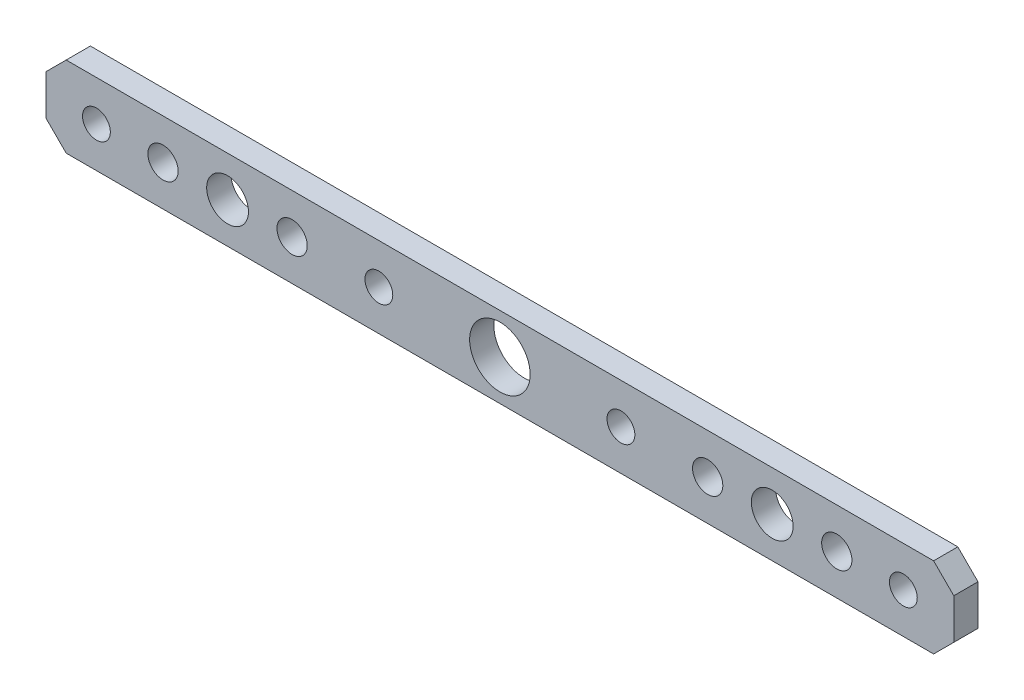
SolidWorks part; units mm, degrees
ref_plane "Front Plane" through (0, 0, 0) normal (0, 0, 1) x (1, 0, 0)
ref_plane "Top Plane" through (0, 0, 0) normal (0, 1, 0) x (1, 0, 0)
ref_plane "Right Plane" through (0, 0, 0) normal (1, 0, 0) x (0, 0, -1)
sketch "Sketch1" plane through (0, 0, 0) normal (0, 0, 1) x (1, 0, 0)
  line L0 (-111.9828, -29.6121) -> (113.0172, -29.6121)
  line L1 (113.0172, -29.6121) -> (113.0172, -9.6121)
  line L3 (-111.9828, -9.6121) -> (-111.9828, -29.6121)
  line L5 (-111.9828, -9.6121) -> (113.0172, -9.6121)
  line L6 (0.5172, -9.6121) -> (0.5172, -29.6121) construction
  circle A0 centre (84.0172, -19.6121) radius 3.75
  circle A1 centre (52.0172, -19.6121) radius 3.75
  circle A2 centre (68.0172, -19.6121) radius 5.1773
  circle A3 centre (-50.9828, -19.6121) radius 3.75
  circle A4 centre (-82.9828, -19.6121) radius 3.75
  circle A5 centre (-66.9828, -19.6121) radius 5.175
  circle A6 centre (30.5172, -19.6121) radius 3.4458
  circle A7 centre (-29.4828, -19.6121) radius 3.4458
  circle A8 centre (100.5172, -19.6121) radius 3.4458
  circle A11 centre (-99.4828, -19.6121) radius 3.4458
  circle A13 centre (0.5172, -19.6121) radius 7.5
  dimension "D6" = 10.35
  dimension "D7" = 10.3546
  dimension "D8" = 7.5
  dimension "D9" = 7.5
  dimension "D10" = 7.5
  dimension "D11" = 7.5
  dimension "D16" = 15
  dimension "D2" = 225
  dimension "D3" = 60
  dimension "D4" = 10
  dimension "D5" = 135
  dimension "D12" = 200
  dimension "D13" = 16
  dimension "D14" = 16
  dimension "D17" = 20
extrude "Boss-Extrude1" add sketch "Sketch1" along normal blind 6
chamfer "Chamfer1" distance 5 angle 45 4 edges at (-111.9828, -29.6121, 3) (-111.9828, -9.6121, 3) (113.0172, -29.6121, 3) (113.0172, -9.6121, 3)
